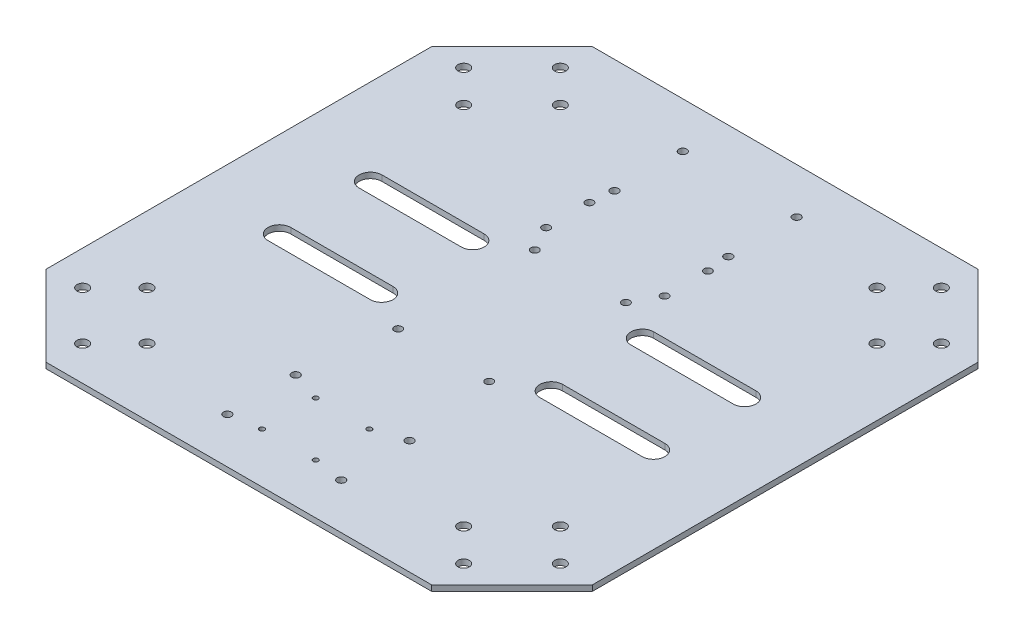
SolidWorks part; units mm, degrees
ref_plane "Front Plane" through (0, 0, 0) normal (0, 0, 1) x (1, 0, 0)
ref_plane "Top Plane" through (0, 0, 0) normal (0, 1, 0) x (1, 0, 0)
ref_plane "Right Plane" through (0, 0, 0) normal (1, 0, 0) x (0, 0, -1)
sketch "Sketch1" plane through (0, 0, 0) normal (0, 1, 0) x (1, 0, 0)
  line L0 (-61.766, 6.7551) -> (-16.8648, 51.6564)
  line L1 (-61.766, 51.6564) -> (243.034, 51.6564)
  line L2 (-61.766, 51.6564) -> (-61.766, -253.1436)
  line L3 (-61.766, -253.1436) -> (243.034, -253.1436)
  line L4 (243.034, 51.6564) -> (243.034, -253.1436)
  line L5 (90.634, 95.069) -> (90.634, -294.9418) construction
  line L6 (-86.5248, -100.7436) -> (277.558, -100.7436) construction
  line L7 (243.034, 6.7551) -> (198.1327, 51.6564)
  line L8 (243.034, -208.2424) -> (198.1327, -253.1436)
  line L9 (-61.766, -208.2424) -> (-16.8648, -253.1436)
  line L10 (137.9303, -75.3436) -> (194.9471, -75.3436) construction
  line L11 (137.9303, -68.9936) -> (194.9471, -68.9936)
  line L12 (137.9303, -81.6936) -> (194.9471, -81.6936)
  line L13 (137.9303, -126.1436) -> (194.9471, -126.1436) construction
  line L14 (137.9303, -132.4936) -> (194.9471, -132.4936)
  line L15 (137.9303, -119.7936) -> (194.9471, -119.7936)
  line L16 (43.3376, -126.1436) -> (-13.6792, -126.1436) construction
  line L17 (43.3376, -132.4936) -> (-13.6792, -132.4936)
  line L18 (43.3376, -119.7936) -> (-13.6792, -119.7936)
  line L19 (43.3376, -75.3436) -> (-13.6792, -75.3436) construction
  line L20 (43.3376, -68.9936) -> (-13.6792, -68.9936)
  line L21 (43.3376, -81.6936) -> (-13.6792, -81.6936)
  arc A0 (137.9303, -68.9936) -> (137.9303, -81.6936) centre (137.9303, -75.3436) ccw
  arc A1 (194.9471, -81.6936) -> (194.9471, -68.9936) centre (194.9471, -75.3436) ccw
  arc A2 (137.9303, -132.4936) -> (137.9303, -119.7936) centre (137.9303, -126.1436) cw
  arc A3 (194.9471, -119.7936) -> (194.9471, -132.4936) centre (194.9471, -126.1436) cw
  arc A4 (43.3376, -132.4936) -> (43.3376, -119.7936) centre (43.3376, -126.1436) ccw
  arc A5 (-13.6792, -119.7936) -> (-13.6792, -132.4936) centre (-13.6792, -126.1436) ccw
  arc A6 (43.3376, -68.9936) -> (43.3376, -81.6936) centre (43.3376, -75.3436) cw
  arc A7 (-13.6792, -81.6936) -> (-13.6792, -68.9936) centre (-13.6792, -75.3436) cw
  point P8 (90.634, 51.6564)
  point P11 (-61.766, -100.7436)
  point P18 (166.4387, -75.3436)
  point P27 (166.4387, -126.1436)
  point P34 (14.8292, -126.1436)
  point P41 (14.8292, -75.3436)
  dimension "D6" = 6.35
  dimension "D1" = 304.8
  dimension "D2" = 304.8
  dimension "D3" = 45
  dimension "D4" = 63.5
  dimension "D5" = 38.1
extrude "Boss-Extrude1" add sketch "Sketch1" along normal blind 3.175 contours L2 L9 L3 L8 L4 L7 L1 L0 A5 L18 A4 L17 A1 L12 A0 L11 L15 A3 L14 A2 L21 A7 L20 A6
sketch "Sketch2" plane through (0, 3.175, 0) normal (0, 1, 0) x (1, 0, 0)
  line L7 (90.634, 51.6564) -> (90.634, -253.1436) construction
  line L8 (-16.8648, 51.6564) -> (198.1327, 51.6564) construction
  line L9 (-16.8648, -253.1436) -> (198.1327, -253.1436) construction
  line L10 (-61.766, -100.7436) -> (243.034, -100.7436) construction
  line L11 (-61.766, 6.7551) -> (-61.766, -208.2424) construction
  line L12 (243.034, 6.7551) -> (243.034, -208.2424) construction
  circle A0 centre (-15.6273, 32.4584) radius 3.175
  circle A1 centre (2.3332, 14.4979) radius 3.175
  circle A2 centre (-24.6076, -12.4429) radius 3.175
  circle A3 centre (-42.5681, 5.5176) radius 3.175
  circle A4 centre (205.8755, -12.4429) radius 3.175
  circle A5 centre (223.836, 5.5176) radius 3.175
  circle A6 centre (178.9347, 14.4979) radius 3.175
  circle A7 centre (196.8952, 32.4584) radius 3.175
  circle A8 centre (-24.6076, -189.0444) radius 3.175
  circle A9 centre (-42.5681, -207.0049) radius 3.175
  circle A10 centre (-15.6273, -233.9457) radius 3.175
  circle A11 centre (2.3332, -215.9852) radius 3.175
  circle A12 centre (223.836, -207.0049) radius 3.175
  circle A13 centre (196.8952, -233.9457) radius 3.175
  circle A14 centre (178.9347, -215.9852) radius 3.175
  circle A15 centre (205.8755, -189.0444) radius 3.175
  dimension "D3" = 6.35
  dimension "D4" = 6.35
  dimension "D5" = 6.35
  dimension "D6" = 6.35
  dimension "D1" = 25.4
  dimension "D2" = 38.1
extrude "Cut-Extrude1" cut sketch "Sketch2" against normal blind 6.35
sketch "Sketch3" plane through (0, 3.175, 0) normal (0, 1, 0) x (1, 0, 0)
  circle A0 centre (65.234, -62.6436) radius 2.159
  circle A1 centre (116.034, -62.6436) radius 2.159
  circle A2 centre (65.234, -138.8436) radius 2.159
  circle A3 centre (116.034, -138.8436) radius 2.159
  dimension "D3" = 4.318
  dimension "D4" = 4.318
  dimension "D5" = 4.318
  dimension "D6" = 4.318
  dimension "D1" = 50.8
  dimension "D2" = 76.2
extrude "Cut-Extrude2" cut sketch "Sketch3" against normal blind 6.35
sketch "Sketch4" plane through (0, 3.175, 0) normal (0, 1, 0) x (1, 0, 0)
  line L0 (90.634, 51.6564) -> (90.634, -36.4614) construction
  line L1 (-16.8648, 51.6564) -> (198.1327, 51.6564) construction
  line L2 (-61.766, -100.7436) -> (257.447, -100.7436) construction
  line L3 (-61.766, 6.7551) -> (-61.766, -208.2424) construction
  circle A0 centre (58.884, 26.2564) radius 2.2225
  circle A1 centre (122.384, 26.2564) radius 2.2225
  circle A2 centre (58.884, -11.8436) radius 2.2225
  circle A3 centre (122.384, -11.8436) radius 2.2225
  circle A4 centre (122.384, -189.6436) radius 2.2225
  circle A5 centre (58.884, -189.6436) radius 2.2225
  circle A6 centre (122.384, -227.7436) radius 2.2225
  circle A7 centre (58.884, -227.7436) radius 2.2225
  dimension "D1" = 4.445
  dimension "D2" = 4.445
  dimension "D3" = 4.445
  dimension "D4" = 4.445
  dimension "D5" = 63.5
  dimension "D6" = 38.1
  dimension "D7" = 31.75
  dimension "D8" = 25.4
extrude "Cut-Extrude3" cut sketch "Sketch4" against normal through all
sketch "Sketch5" plane through (0, 0, 0) normal (0, -1, 0) x (-1, 0, 0)
  line L0 (-243.034, -100.7436) -> (61.766, -100.7436) construction
  line L1 (-243.034, 6.7551) -> (-243.034, -208.2424) construction
  line L2 (61.766, 6.7551) -> (61.766, -208.2424) construction
  point P6 (0, 0)
  point P7 (0, 0)
  point P8 (0, 0)
sketch "Sketch9" plane through (0, 0, 0) normal (0, -1, 0) x (1, 0, 0)
  line L0 (90.634, -51.6564) -> (90.634, 253.1436) construction
  line L1 (-16.8648, -51.6564) -> (198.1327, -51.6564) construction
  line L2 (-16.8648, 253.1436) -> (198.1327, 253.1436) construction
sketch "Sketch10" plane through (0, 0, 0) normal (0, -1, 0) x (-1, 0, 0)
  line L0 (-90.634, 51.6564) -> (-90.634, -253.1436) construction
  line L1 (-90.634, -253.1436) -> (-90.634, -160.8193) construction
  circle A0 centre (-105.62, -195.2224) radius 1.397
  circle A1 centre (-105.62, -225.1944) radius 1.397
  circle A2 centre (-75.648, -225.1944) radius 1.397
  circle A3 centre (-75.648, -195.2224) radius 1.397
  dimension "D1" = 29.972
  dimension "D3" = 2.794
  dimension "D4" = 2.794
  dimension "D2" = 14.986
extrude "Cut-Extrude4" cut sketch "Sketch10" against normal through all
sketch "Sketch11" plane through (0, 0, 0) normal (0, -1, 0) x (1, 0, 0)
  line L0 (-16.8648, -51.6564) -> (198.1327, -51.6564) construction
  line L1 (90.634, -51.6564) -> (90.634, 70.724) construction
  line L2 (90.634, -51.6564) -> (90.634, 253.1436) construction
  circle A0 centre (123.654, 24.5436) radius 2.159
  circle A1 centre (123.654, 48.6736) radius 2.159
  circle A2 centre (57.614, 48.6736) radius 2.159
  circle A3 centre (57.614, 24.5436) radius 2.159
  point P19 (302.6204, -53.7223)
  dimension "D1" = 33.02
  dimension "D2" = 24.13
  dimension "D3" = 4.318
  dimension "D4" = 76.2
extrude "Cut-Extrude6" cut sketch "Sketch11" against normal through all contours A1 | A2 | A0 | A3
